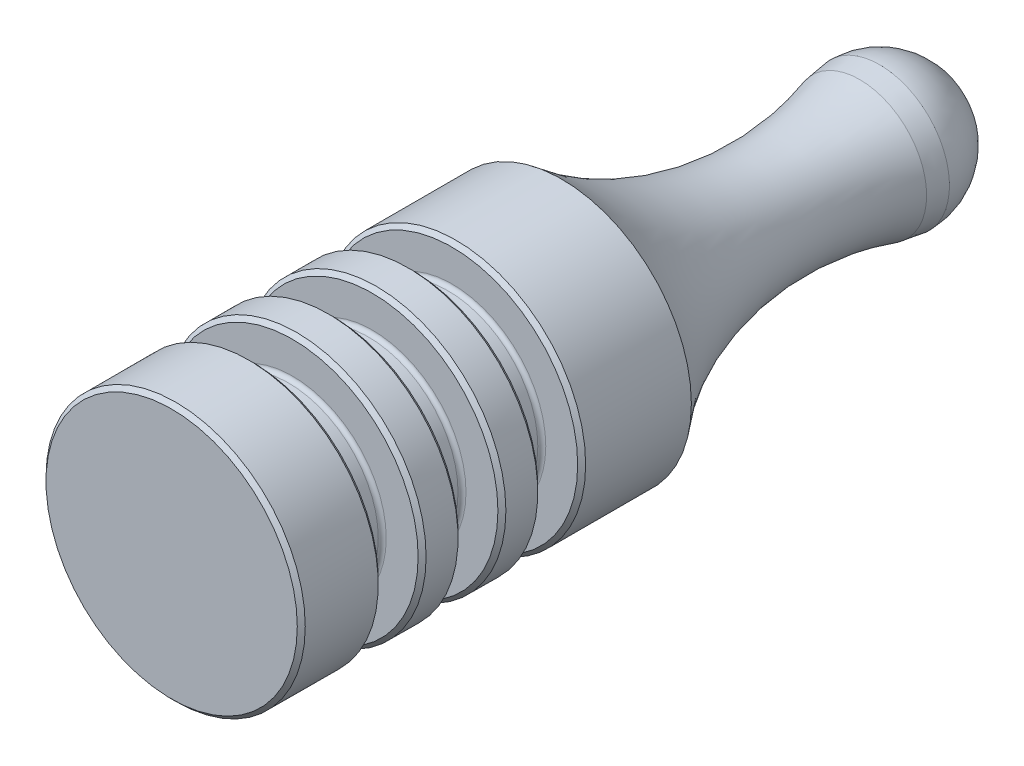
SolidWorks part; units mm, degrees
material "6061 Legierung"
ref_plane "Ebene vorne" through (0, 0, 0) normal (0, 0, 1) x (1, 0, 0)
ref_plane "Ebene oben" through (0, 0, 0) normal (0, 1, 0) x (1, 0, 0)
ref_plane "Ebene rechts" through (0, 0, 0) normal (1, 0, 0) x (0, 0, -1)
sketch "Skizze1" plane through (0, 0, 0) normal (0, 0, 1) x (1, 0, 0)
  circle A0 centre (0, 0) radius 6.5
  dimension "D1" = 13
extrude "Aufsatz-Linear austragen1" add sketch "Skizze1" along normal blind 35.5
sketch "Skizze2" plane through (0, 0, 0) normal (1, 0, 0) x (0, 0, -1)
  line L0 (0, 6.5) -> (-35.5, 6.5) construction
  line L1 (-31.44, 6.5) -> (-29.44, 6.5)
  line L2 (-31.44, 6.5) -> (-31.44, 4.5)
  line L3 (-31.44, 4.5) -> (-29.44, 4.5)
  line L4 (-29.44, 6.5) -> (-29.44, 4.5)
  line L5 (-35.5, 6.5) -> (-35.5, -6.5) construction
  line L6 (-28.44, 8.4156) -> (-28.44, -8.2265) construction
  line L7 (-27.44, 6.5) -> (-27.44, 4.5)
  line L8 (-25.44, 4.5) -> (-27.44, 4.5)
  line L9 (-25.44, 6.5) -> (-25.44, 4.5)
  line L10 (-25.44, 6.5) -> (-27.44, 6.5)
  line L11 (-24.44, 8.0674) -> (-24.44, -8.6357) construction
  line L12 (-23.44, 6.5) -> (-21.44, 6.5)
  line L13 (-23.44, 6.5) -> (-23.44, 4.5)
  line L14 (-23.44, 4.5) -> (-21.44, 4.5)
  line L15 (-21.44, 6.5) -> (-21.44, 4.5)
  dimension "D1" = 2
  dimension "D2" = 2
  dimension "D3" = 4.06
  dimension "D4" = 4.5
  dimension "D5" = 1
  dimension "D6" = 1
revolve "Schnitt-Rotation1" cut sketch "Skizze2" angle 360 about axis through (0, 0, 35.5) along (0, 0, -1)
sketch "Skizze5" plane through (0, 0, 0) normal (1, 0, 0) x (0, 0, -1)
  line L0 (0, 6.5) -> (-21.44, 6.5) construction
  line L1 (-1, 3.355) -> (0, 3.5)
  line L2 (0, -6.5) -> (0, 6.5) construction
  line L3 (-21.44, 0) -> (0, 0) construction
  line L4 (-15.94, 6.5) -> (0, 6.5)
  line L5 (0, 6.5) -> (0, 3.5)
  arc A0 (-15.94, 6.5) -> (-1, 3.355) centre (-5.5734, 18.6874) ccw
  dimension "D5" = 16
  dimension "D1" = 3.5
  dimension "D2" = 3.355
  dimension "D3" = 1
  dimension "D4" = 15.94
revolve "Schnitt-Rotation2" cut sketch "Skizze5" angle 360 about axis through (0, 0, 35.5) along (0, 0, -1)
sketch "Skizze6" plane through (0, 0, 0) normal (1, 0, 0) x (0, 0, -1)
  line L0 (3.5, 0) -> (0, 0)
  line L1 (0, 0) -> (0, 3.5)
  arc A0 (0, 3.5) -> (3.5, 0) centre (0, 0) cw
  dimension "D1" = 3.5
revolve "Rotation1" add sketch "Skizze6" angle 360
chamfer "Fase1" distance 0.2 7 edges at (6.5, 0, 21.44) (6.5, 0, 23.44) (6.5, 0, 25.44) (6.5, 0, 27.44) (6.5, 0, 29.44) (6.5, 0, 31.44) (6.5, 0, 35.5)
fillet "Verrundung1" radius 0.2 6 edges at (4.5, 0, 21.44) (4.5, 0, 25.44) (4.5, 0, 29.44) (4.5, 0, 23.44) (4.5, 0, 27.44) (4.5, 0, 31.44)
